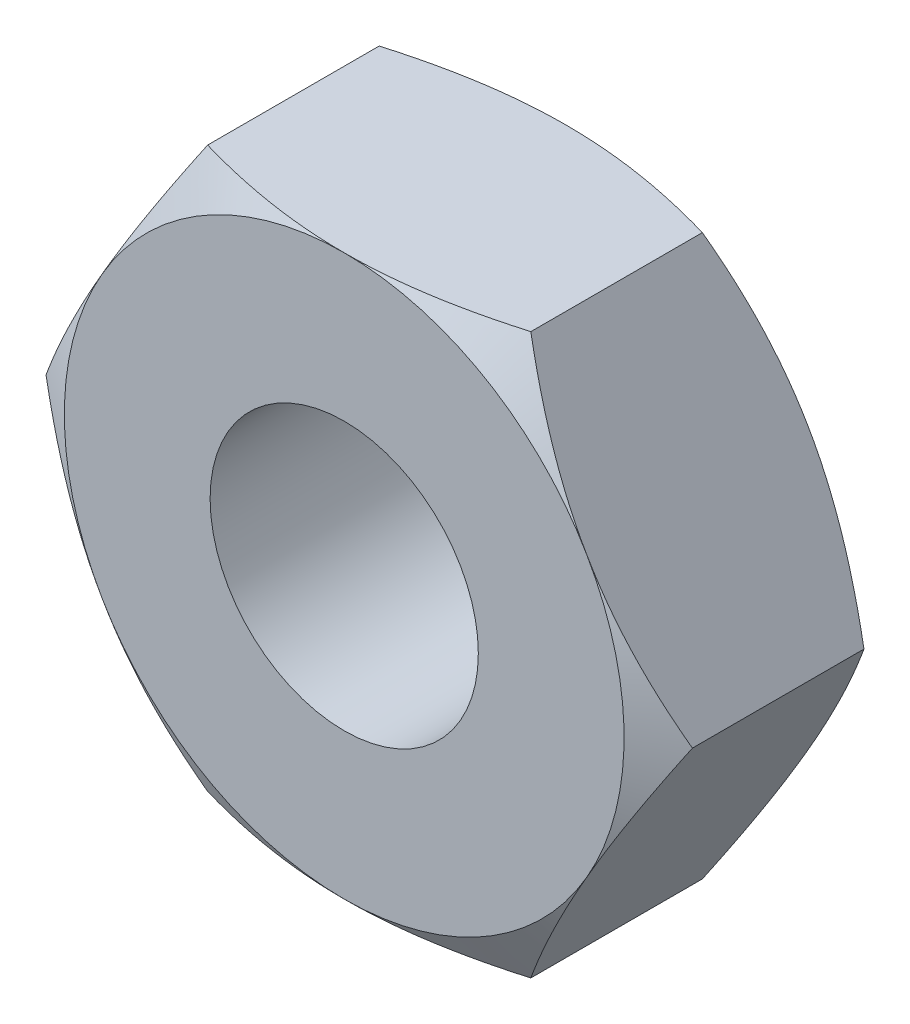
SolidWorks part; units mm, degrees
material "AISI 316 Annealed Stainless Steel Bar (SS)"
ref_plane "Front Plane" through (0, 0, 0) normal (0, 0, 1) x (1, 0, 0)
ref_plane "Top Plane" through (0, 0, 0) normal (0, 1, 0) x (1, 0, 0)
ref_plane "Right Plane" through (0, 0, 0) normal (1, 0, 0) x (0, 0, -1)
sketch "Sketch1" plane through (0, 0, 0) normal (0, 0, 1) x (1, 0, 0)
  line L1 (-1.3856, 2.4) -> (-2.7713, 0)
  line L2 (-2.7713, 0) -> (-1.3856, -2.4)
  line L3 (-1.3856, -2.4) -> (1.3856, -2.4)
  line L4 (1.3856, -2.4) -> (2.7713, 0)
  line L5 (2.7713, 0) -> (1.3856, 2.4)
  line L6 (1.3856, 2.4) -> (-1.3856, 2.4)
  circle A0 centre (0, 0) radius 2.4 construction
  circle A1 centre (0, 0) radius 1.15
  dimension "D2" = 2.3
  dimension "D1" = 4.8
extrude "Boss-Extrude1" add sketch "Sketch1" along normal blind 1.9
sketch "Sketch2" plane through (0, 0, 1.9) normal (0, 0, 1) x (1, 0, 0)
  circle A0 centre (0, 0) radius 2.4 construction
  circle A1 centre (0, 0) radius 2.4
extrude "Cut-Extrude1" cut sketch "Sketch2" against normal blind 10 draft 60 flip side to cut
sketch "Sketch3" plane through (0, 0, 0) normal (0, 0, -1) x (-1, 0, 0)
  circle A0 centre (0, 0) radius 2.4 construction
  circle A1 centre (0, 0) radius 2.4
extrude "Cut-Extrude2" cut sketch "Sketch3" against normal blind 10 draft 60 flip side to cut
